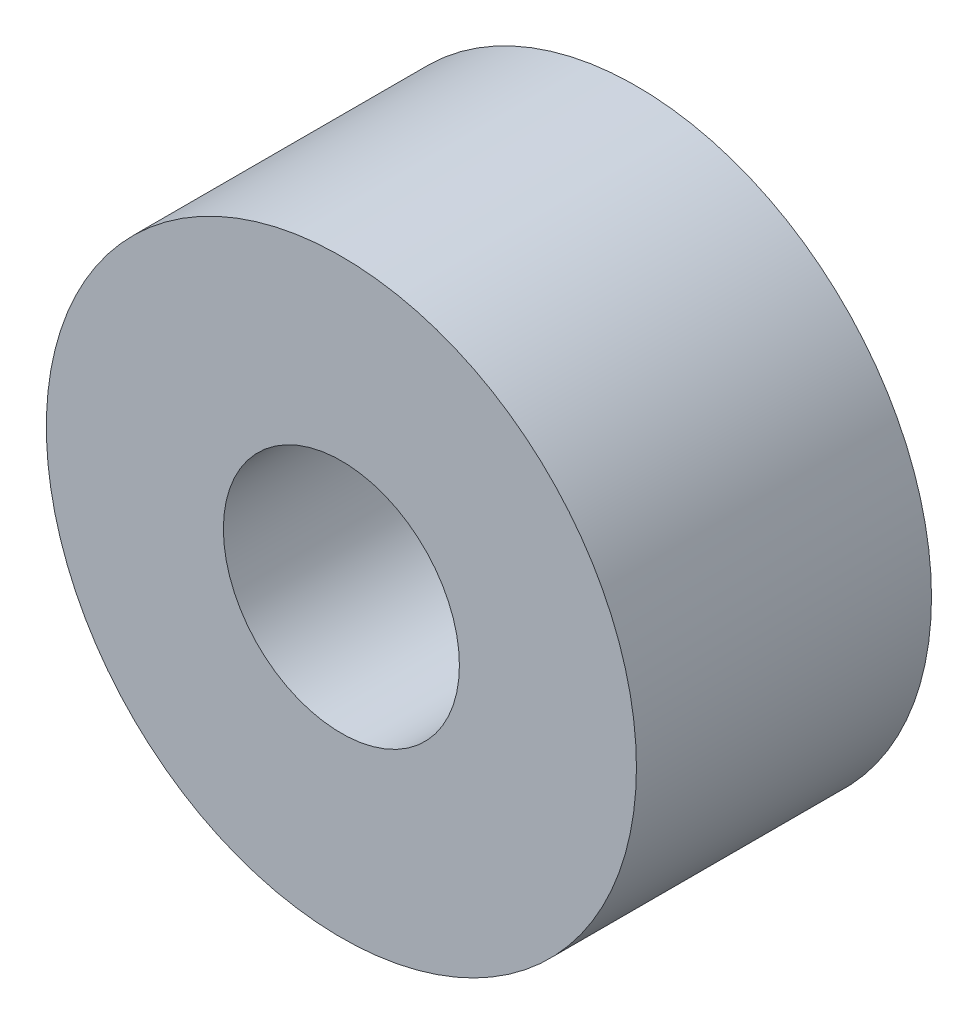
SolidWorks part; units mm, degrees
ref_plane "前视基准面" through (0, 0, 0) normal (0, 0, 1) x (1, 0, 0)
ref_plane "上视基准面" through (0, 0, 0) normal (0, 1, 0) x (1, 0, 0)
ref_plane "右视基准面" through (0, 0, 0) normal (1, 0, 0) x (0, 0, -1)
sketch "草图1" plane through (0, 0, 0) normal (0, 0, 1) x (1, 0, 0)
  circle A0 centre (0, 0) radius 1
  circle A1 centre (0, 0) radius 2.5
  dimension "D1" = 2
  dimension "D2" = 5
extrude "凸台-拉伸1" add sketch "草图1" along normal mid plane 2.5
